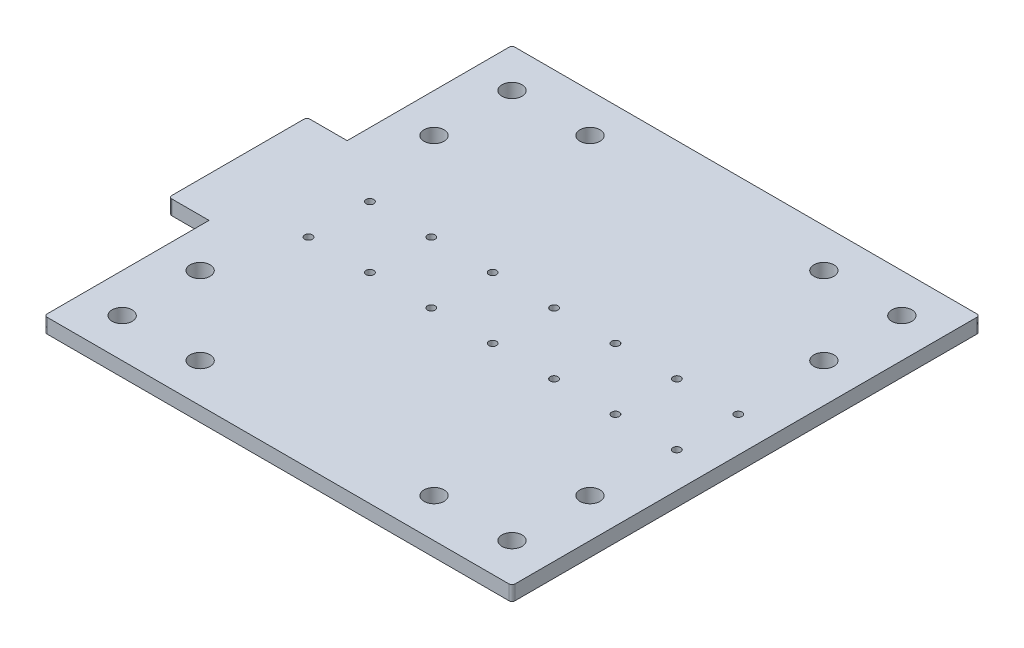
SolidWorks part; units mm, degrees
ref_plane "Front Plane" through (0, 0, 0) normal (0, 0, 1) x (1, 0, 0)
ref_plane "Top Plane" through (0, 0, 0) normal (0, 1, 0) x (1, 0, 0)
ref_plane "Right Plane" through (0, 0, 0) normal (1, 0, 0) x (0, 0, -1)
sketch "Sketch1" plane through (0, 0, 0) normal (0, 1, 0) x (1, 0, 0)
  line L0 (152.4, -76.2) -> (0, -76.2) construction
  line L1 (0, 0) -> (152.4, 0)
  line L2 (0, 0) -> (0, -152.4)
  line L3 (0, -152.4) -> (152.4, -152.4)
  line L4 (152.4, 0) -> (152.4, -152.4)
  line L5 (-6.35, 6.35) -> (158.75, 6.35) construction
  line L6 (-6.35, 6.35) -> (-6.35, -158.75) construction
  line L7 (-6.35, -158.75) -> (158.75, -158.75) construction
  line L8 (158.75, 6.35) -> (158.75, -158.75) construction
  line L14 (0, -53.7) -> (-13.1, -53.7)
  line L15 (0, -53.7) -> (0, -98.7)
  line L16 (0, -98.7) -> (-13.1, -98.7)
  line L17 (-13.1, -53.7) -> (-13.1, -98.7)
  circle A4 centre (12.7, -12.7) radius 3.2639
  circle A5 centre (139.7, -12.7) radius 3.2639
  circle A6 centre (139.7, -139.7) radius 3.2639
  circle A7 centre (12.7, -139.7) radius 3.2639
  circle A8 centre (38.1, -12.7) radius 3.2639
  circle A9 centre (114.3, -12.7) radius 3.2639
  circle A10 centre (139.7, -38.1) radius 3.2639
  circle A11 centre (139.7, -114.3) radius 3.2639
  circle A12 centre (114.3, -139.7) radius 3.2639
  circle A13 centre (38.1, -139.7) radius 3.2639
  circle A14 centre (12.7, -114.3) radius 3.2639
  circle A15 centre (12.7, -38.1) radius 3.2639
  point P5 (12.7, -12.7)
  point P6 (139.7, -12.7)
  point P7 (139.7, -139.7)
  point P8 (12.7, -139.7)
  point P40 (38.1, -12.7)
  point P41 (12.7, -38.1)
  point P42 (139.7, -38.1)
  point P43 (114.3, -12.7)
  point P44 (139.7, -114.3)
  point P45 (114.3, -139.7)
  point P46 (38.1, -139.7)
  point P47 (12.7, -114.3)
  point P51 (0, -61.9074)
  point P52 (0, 0)
  point P53 (-13.1, -76.2)
  dimension "D7" = 6.5278
  dimension "D1" = 127
  dimension "D2" = 127
  dimension "D3" = 12.7
  dimension "D4" = 12.7
  dimension "D5" = 12.7
  dimension "D6" = 12.7
  dimension "D8" = 165.1
  dimension "D10" = 6.35
  dimension "D11" = 152.4
  dimension "D12" = 6.35
  dimension "D13" = 38.1
  dimension "D15" = 38.1
  dimension "D14" = 38.1
  dimension "D16" = 38.1
  dimension "D17" = 45
  dimension "D18" = 13.1
extrude "Boss-Extrude1" add sketch "Sketch1" along normal blind 4.7625 contours L4 L1 L2 L3 A15 A14 A13 A12 A11 A10 A9 A8 A7 A6 A5 A4 | L1 L17 L16 L15
ref_plane "Top of Object Plane" through (0, 4.7625, 0) normal (0, 1, 0) x (1, 0, 0)
ref_plane "Lower Object Plane" through (0, -1.0795, 0) normal (0, 1, 0) x (1, 0, 0)
fillet "Fillet1" radius 1 6 edges at (152.4, 2.3813, 152.4) (152.4, 2.3813, 0) (0, 2.3813, 0) (0, 2.3813, 152.4) (-13.1, 2.3813, 98.7) (-13.1, 2.3813, 53.7)
sketch "Sketch11" plane through (0, 4.7625, 0) normal (0, 1, 0) x (1, 0, 0)
  line L0 (20.905, -77.2) -> (0, -77.2) construction
  line L1 (0, -1) -> (0, -53.7) construction
  line L2 (19.53, -67.2) -> (22.28, -67.2) construction
  line L3 (20.905, -67.2) -> (20.905, -87.2) construction
  line L4 (14.4, -54.7) -> (115.6, -54.7) construction
  line L5 (1, -152.4) -> (151.4, -152.4) construction
  line L6 (100.905, -67.2) -> (20.905, -67.2) construction
  line L7 (14.4, -54.7) -> (14.4, -99.7) construction
  line L8 (14.4, -99.7) -> (115.6, -99.7) construction
  line L9 (115.6, -54.7) -> (115.6, -99.7) construction
  line L10 (19.53, -65.4) -> (22.28, -65.4) construction
  line L11 (19.53, -69) -> (22.28, -69) construction
  line L12 (19.53, -87.2) -> (22.28, -87.2) construction
  line L13 (19.53, -85.4) -> (22.28, -85.4) construction
  line L14 (19.53, -89) -> (22.28, -89) construction
  line L21 (99.53, -67.2) -> (102.28, -67.2) construction
  line L22 (99.53, -65.4) -> (102.28, -65.4) construction
  line L23 (99.53, -69) -> (102.28, -69) construction
  line L27 (99.53, -87.2) -> (102.28, -87.2) construction
  line L28 (99.53, -85.4) -> (102.28, -85.4) construction
  line L29 (99.53, -89) -> (102.28, -89) construction
  line L30 (65, -54.7) -> (65, -99.7) construction
  circle A10 centre (20.905, -87.2) radius 1
  circle A11 centre (20.905, -67.2) radius 1
  circle A12 centre (40.905, -87.2) radius 1
  circle A13 centre (40.905, -67.2) radius 1
  circle A14 centre (60.905, -87.2) radius 1
  circle A15 centre (60.905, -67.2) radius 1
  circle A16 centre (80.905, -87.2) radius 1
  circle A17 centre (80.905, -67.2) radius 1
  circle A18 centre (100.905, -87.2) radius 1
  circle A19 centre (100.905, -67.2) radius 1
  arc A20 (19.53, -65.4) -> (19.53, -69) centre (19.53, -67.2) ccw construction
  arc A21 (22.28, -69) -> (22.28, -65.4) centre (22.28, -67.2) ccw construction
  arc A22 (19.53, -85.4) -> (19.53, -89) centre (19.53, -87.2) ccw construction
  arc A23 (22.28, -89) -> (22.28, -85.4) centre (22.28, -87.2) ccw construction
  arc A28 (99.53, -65.4) -> (99.53, -69) centre (99.53, -67.2) ccw construction
  arc A29 (102.28, -69) -> (102.28, -65.4) centre (102.28, -67.2) ccw construction
  arc A32 (99.53, -85.4) -> (99.53, -89) centre (99.53, -87.2) ccw construction
  arc A33 (102.28, -89) -> (102.28, -85.4) centre (102.28, -87.2) ccw construction
  circle A34 centre (120.905, -87.2) radius 1
  circle A35 centre (120.905, -67.2) radius 1
  circle A36 centre (140.905, -87.2) radius 1
  circle A37 centre (140.905, -67.2) radius 1
  point P5 (65, -77.2)
  point P19 (20.905, -67.2)
  point P26 (20.905, -87.2)
  point P38 (20.905, -77.2)
  point P70 (100.905, -67.2)
  point P84 (100.905, -87.2)
  dimension "D8" = 65
  dimension "D10" = 2
  dimension "D16" = 1.8
  dimension "D21" = 13.32
  dimension "D9" = 20
  dimension "D11" = 75.2
  dimension "D12" = 101.2
  dimension "D14" = 20
  dimension "D15" = 45
  dimension "D17" = 2.75
  dimension "D18" = 5.13
  dimension "D19" = 20
  dimension "D20" = 12.5
  dimension "D3" = 20.905
  dimension "D13" = 7
extrude "Cut-Extrude1" cut sketch "Sketch11" against normal up to surface (4.7625 mm away) up to face at (12.7, 0, 41.3639)
sketch "Sketch12" plane through (0, 4.7625, 0) normal (0, 1, 0) x (1, 0, 0)
  line L0 (-13.1, -76.2) -> (152.4, -76.2) construction
  line L2 (152.4, -1) -> (152.4, -151.4) construction
  line L3 (-13.1, -54.7) -> (-13.1, -97.7) construction
  point P6 (0, 0)
  point P7 (-13.1, -76.2)
hole_wizard "M3x0.5 Tapped Hole1" positions "3DSketch1" profile "Sketch13" tap size "M3x0.5" standard "ANSI Metric" end condition through all
sketch3d "3DSketch1"
  circle A0 centre (20.905, 4.7625, 67.2) radius 1 construction
  point P0 (20.905, 4.7625, 67.2)
  point P5 (20.905, 5.7625, 67.2)
sketch "Sketch13" plane through (20.905, 4.7625, 67.2) normal (1, 0, 0) x (0, 0, 1)
  line L0 (0, 0) -> (0, 4.7625)
  line L1 (0, 4.7625) -> (1.25, 4.7625)
  line L2 (1.25, 4.7625) -> (1.25, 0)
  line L5 (1.25, 0) -> (0, 0)
  line L11 (0, -6.35) -> (0, 107.95) construction
  dimension "Thru Tap Drill Dia." = 2.5
  dimension "Thru Tap Drill Depth" = 4.7625
cosmetic thread "Hole Thread1" parameters "D2"=3
pattern_linear "LPattern1" count 7 spacing 20 along (1, 0, 0) count 2 spacing 20 along (0, 0, 1) of "M3x0.5 Tapped Hole1"
cosmetic thread "Hole Thread2" parameters "D2"=3
cosmetic thread "Hole Thread3" parameters "D2"=3
cosmetic thread "Hole Thread4" parameters "D2"=3
cosmetic thread "Hole Thread5" parameters "D2"=3
cosmetic thread "Hole Thread6" parameters "D2"=3
cosmetic thread "Hole Thread7" parameters "D2"=3
cosmetic thread "Hole Thread8" parameters "D2"=3
cosmetic thread "Hole Thread9" parameters "D2"=3
cosmetic thread "Hole Thread10" parameters "D2"=3
cosmetic thread "Hole Thread11" parameters "D2"=3
cosmetic thread "Hole Thread12" parameters "D2"=3
cosmetic thread "Hole Thread13" parameters "D2"=3
cosmetic thread "Hole Thread14" parameters "D2"=3
equation "\"D2@Sketch1\"=\"D1@Sketch1\""
equation "\"D4@Sketch1\"=\"D3@Sketch1\""
equation "\"D5@Sketch1\"=\"D3@Sketch1\""
equation "\"D6@Sketch1\"=\"D5@Sketch1\""
equation "\"D9@Sketch1\"=\"D8@Sketch1\""
equation "\"D12@Sketch1\"=\"D10@Sketch1\""
equation "\"Ball_rest_location\"= 0"
equation "\"D15@Sketch1\"=\"D13@Sketch1\""
equation "\"D14@Sketch1\"=\"D13@Sketch1\""
equation "\"D16@Sketch1\"=\"D13@Sketch1\""
equation "\"Outer_circle_Dia\"= 0"
